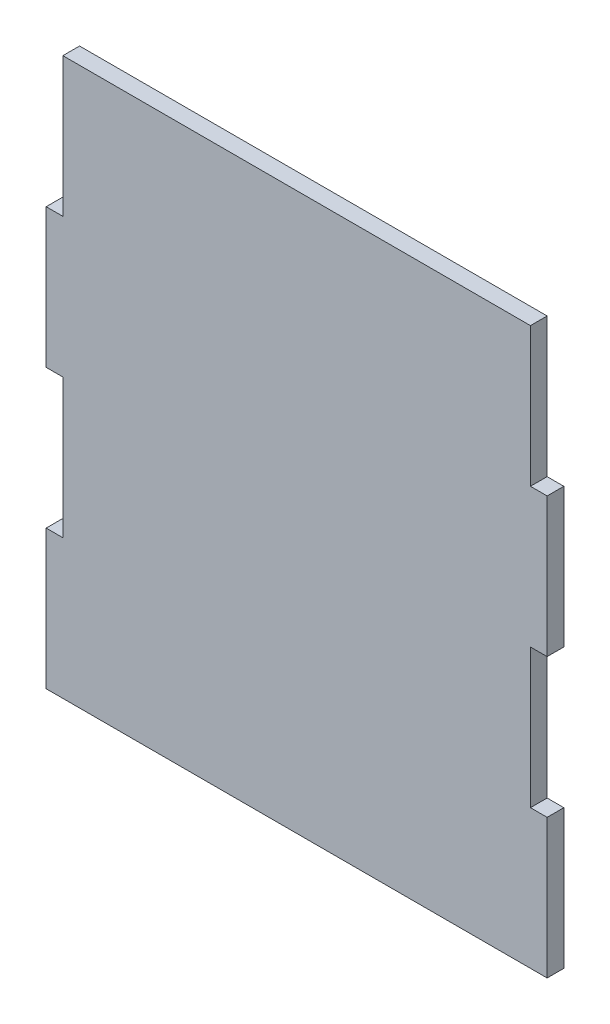
SolidWorks part; units mm, degrees
ref_plane "Plan de face" through (0, 0, 0) normal (0, 0, 1) x (1, 0, 0)
ref_plane "Plan de dessus" through (0, 0, 0) normal (0, 1, 0) x (1, 0, 0)
ref_plane "Plan de droite" through (0, 0, 0) normal (1, 0, 0) x (0, 0, -1)
sketch "Esquisse1" plane through (0, 0, 0) normal (0, 0, 1) x (1, 0, 0)
  line L1 (0, 0) -> (90, 0)
  line L2 (0, 0) -> (0, 100)
  line L3 (0, 100) -> (90, 100)
  line L4 (90, 0) -> (90, 100)
  dimension "D1" = 100
  dimension "D2" = 90
extrude "Boss.-Extru.1" add sketch "Esquisse1" along normal blind 3
sketch "Esquisse2" plane through (0, 0, 3) normal (0, 0, 1) x (1, 0, 0)
  line L0 (0, 100) -> (0, 0) construction
  line L1 (0, 100) -> (3, 100)
  line L2 (0, 100) -> (0, 75)
  line L3 (0, 75) -> (3, 75)
  line L4 (3, 100) -> (3, 75)
  line L5 (0, 50) -> (3, 50)
  line L6 (0, 50) -> (0, 25)
  line L7 (0, 25) -> (3, 25)
  line L8 (3, 50) -> (3, 25)
  line L9 (90, 0) -> (90, 100) construction
  line L10 (90, 100) -> (87, 100)
  line L11 (90, 100) -> (90, 75)
  line L12 (90, 75) -> (87, 75)
  line L13 (87, 100) -> (87, 75)
  line L14 (90, 50) -> (87, 50)
  line L15 (90, 50) -> (90, 25)
  line L16 (90, 25) -> (87, 25)
  line L17 (87, 50) -> (87, 25)
  dimension "D1" = 3
  dimension "D2" = 25
  dimension "D3" = 25
  dimension "D4" = 25
  dimension "D5" = 3
  dimension "D6" = 25
  dimension "D7" = 3
  dimension "D8" = 3
  dimension "D9" = 25
  dimension "D10" = 25
extrude "Enlèv. mat.-Extru.1" cut sketch "Esquisse2" against normal blind 3
sketch "Esquisse3" plane through (0, 0, 3) normal (0, 0, 1) x (1, 0, 0)
  line L1 (3, 75) -> (87, 75)
  line L2 (3, 75) -> (3, 100)
  line L3 (3, 100) -> (87, 100)
  line L4 (87, 75) -> (87, 100)
